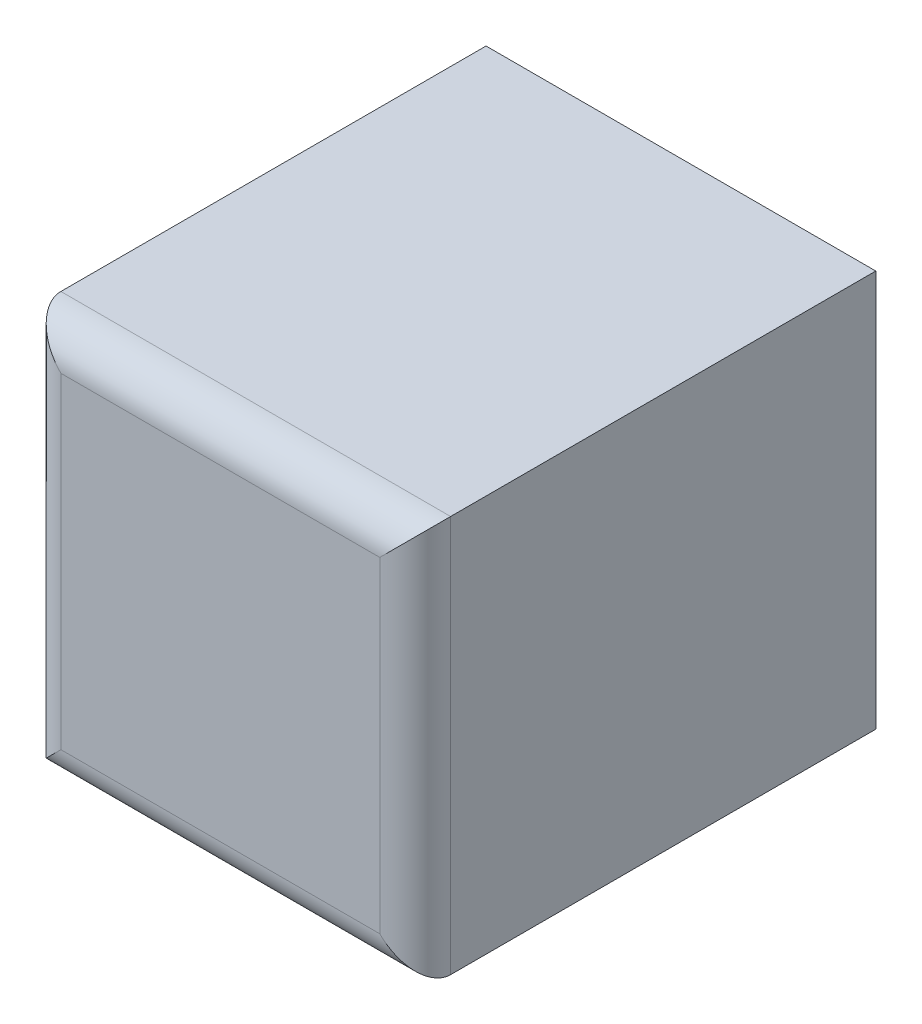
SolidWorks part; units mm, degrees
ref_plane "前视基准面" through (0, 0, 0) normal (0, 0, 1) x (1, 0, 0)
ref_plane "上视基准面" through (0, 0, 0) normal (0, 1, 0) x (1, 0, 0)
ref_plane "右视基准面" through (0, 0, 0) normal (1, 0, 0) x (0, 0, -1)
sketch "草图1" plane through (0, 0, 0) normal (0, 0, 1) x (1, 0, 0)
  line L1 (0, 0) -> (55, 0)
  line L2 (0, 0) -> (0, -56)
  line L3 (0, -56) -> (55, -56)
  line L4 (55, 0) -> (55, -56)
  dimension "D1" = 55
  dimension "D2" = 56
extrude "凸台-拉伸1" add sketch "草图1" along normal blind 65
fillet "圆角1" radius 5 4 edges at (27.5, -56, 65) (55, -28, 65) (0, -28, 65) (27.5, 0, 65)
